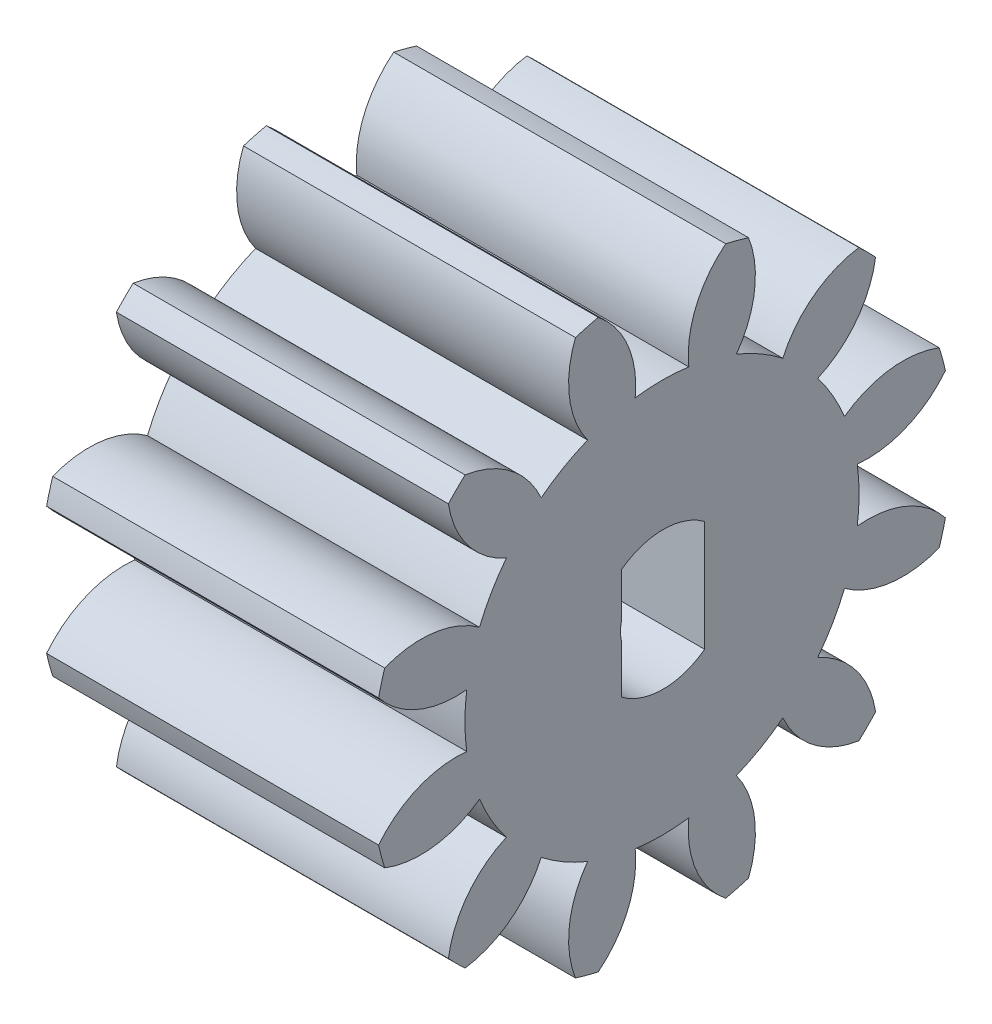
SolidWorks part; units mm, degrees
ref_plane "Plane1" through (0, 0, 0) normal (0, 0, 1) x (1, 0, 0)
ref_plane "Plane2" through (0, 0, 0) normal (0, 1, 0) x (1, 0, 0)
ref_plane "Plane3" through (0, 0, 0) normal (1, 0, 0) x (0, 0, -1)
sketch "HoldingSke" plane through (0, 0, 0) normal (0, 1, 0) x (1, 0, 0)
  line L0 (0, 0) -> (0.6521, -0.1386)
  line L1 (-15, 0) -> (100, 0) construction
  line L2 (0, 0) -> (-2.1039, 2.3779)
  line L3 (0, 0) -> (-11.863, 4.5341)
  line L4 (0, 0) -> (8.4473, 1.7955)
  line L5 (0, 0) -> (-46.8476, -17.4728)
  line L6 (0, 0) -> (-9.9476, -6.7116)
  line L7 (-2.1039, 2.3779) -> (8.6586, 51.2059)
  line L8 (-76.2, 54.61) -> (-75.7, 54.61)
  line L9 (-67.7845, 28.3722) -> (-49.3413, 33.142)
  line L10 (-76.2, 71.12) -> (104.1128, 71.12)
  line L11 (0, 0) -> (-12, 0)
  line L12 (-76.2, 101.6) -> (-76.147, 101.6)
  line L13 (24.9733, 27.94) -> (52.9518, 28.4284)
  line L14 (24.9733, 27.94) -> (24.9743, 27.94)
  line L15 (24.9733, 27.94) -> (100.4006, 29.5858)
  line L16 (-63.627, -1.5) -> (-12.827, -1.5)
  circle A0 centre (0, 0) radius 1.5
  circle A1 centre (0, 0) radius 7.124
  circle A2 centre (0, 0) radius 37.5
  circle A3 centre (0, 0) radius 1.5
  dimension "MHD" = 14.248
  dimension "Hub_dia" = 75
  dimension "Bore" = 3
  dimension "MBD" = 3
  dimension "Num_teeth" = 12
  dimension "Pitch" = 0.6667
  dimension "Overall_len" = 50
  dimension "Show_teeth" = 12
  dimension "Thickness" = 12
  dimension "OAL" = 50.0001
  dimension "T_dim" = 0.5
  dimension "Ap" = 14.5
  dimension "H" = 19.05
  dimension "Pitch_radius" = 180.3128
  dimension "Width" = 12
  dimension "Backlash" = 0.053
  dimension "Addendum_fac" = 1
  dimension "Dedendum_fac" = 1.25
  dimension "Clearance_fac" = 0.25
  dimension "Dedendum_add" = 0.001
  dimension "Module" = 1.5
sketch "BasProSke" plane through (0, 0, 0) normal (0, 1, 0) x (1, 0, 0)
  line L0 (-10, 0) -> (60, 0) construction
  line L1 (0, 0) -> (0, 10.5)
  line L2 (0, 0) -> (12, 0)
  line L3 (12, 0) -> (12, 10.5)
  line L4 (12, 10.5) -> (0, 10.5)
  dimension "Thickness" = 12
  dimension "Diameter" = 21
revolve "Base-Revolve" add sketch "BasProSke" angle 360 about L0
sketch "TooCutSke" plane through (0, 0, 0) normal (1, 0, 0) x (0, 0, -1)
  line L1 (0, 0) -> (0, 107) construction
  line L2 (0, 0) -> (-1.2674, 8.9103) construction
  line L3 (0, 0) -> (-4.625, 17.2606) construction
  line L4 (-1.2674, 8.9103) -> (-2.3125, 8.6303) construction
  arc A0 (0.9689, 7.0578) -> (-0.9689, 7.0578) centre (0, 0) ccw
  arc A1 (2.3286, 10.2646) -> (-2.3286, 10.2646) centre (0, 0) ccw
  circle A2 centre (0, 0) radius 9 construction
  circle A3 centre (0, 0) radius 8.7133 construction
  arc A4 (-0.9689, 7.0578) -> (-2.3286, 10.2646) centre (-4.5495, 7.4313) ccw
  arc A5 (2.3286, 10.2646) -> (0.9689, 7.0578) centre (4.5495, 7.4313) ccw
  dimension "Root_dia" = 14.248
  dimension "Overcut_dia" = 21.0508
  dimension "Pitch_dia" = 18
  dimension "Base_dia" = 17.4267
  dimension "Flank_rad" = 3.6
  dimension "Half_ang" = 15
  dimension "Half_CT" = 1.082
extrude "ToothCut" cut sketch "TooCutSke" along normal through all
fillet "Breaks" [suppressed] radius 0.03
fillet "RootFillets" [suppressed] radius 0.376
pattern_circular "TeethCuts" count 12 every 30 about axis through (-10, 0, 0) along (1, 0, 0) of "ToothCut", "RootFillets", "Breaks"
sketch "HubNeaOneSke" plane through (0, 0, 0) normal (-1, 0, 0) x (0, 0, 1)
  circle A0 centre (0, 0) radius 7.124
  dimension "Diameter" = 14.248
extrude "HubNearOne" [suppressed] add sketch "HubNeaOneSke" along normal blind 38.0001
sketch "HubNeaBotSke" plane through (0, 0, 0) normal (-1, 0, 0) x (0, 0, 1)
  circle A0 centre (0, 0) radius 7.124
  dimension "Diameter" = 14.248
extrude "HubNearBoth" [suppressed] add sketch "HubNeaBotSke" along normal blind 19
ref_plane "FarPln" through (12, 0, 0) normal (1, 0, 0) x (0, 0, -1)
sketch "HubFarSke" plane through (12, 0, 0) normal (1, 0, 0) x (0, 0, -1)
  circle A0 centre (0, 0) radius 7.124
  dimension "Diameter" = 14.248
extrude "HubFar" [suppressed] add sketch "HubFarSke" along normal blind 19
sketch "BorSke" plane through (0, 0, 0) normal (1, 0, 0) x (0, 0, -1)
  circle A0 centre (0, 0) radius 1.5
  dimension "Diameter" = 3
extrude "Bore" cut sketch "BorSke" along normal mid plane 100.0001
sketch "KeySke" plane through (0, 0, 0) normal (1, 0, 0) x (0, 0, -1)
  line L0 (-0.6, 0) -> (-0.6, 2)
  line L1 (-0.6, 2) -> (0.6, 2)
  line L2 (0.6, 2) -> (0.6, 0)
  line L3 (0, 0) -> (0, 34) construction
  line L4 (-0.6, 0) -> (0.6, 0)
  dimension "Offset" = 2
extrude "Keyway" [suppressed] cut sketch "KeySke" along normal mid plane 100.0001
pattern_circular "Keyway2" [suppressed] count 2 every 90 about axis through (-10, 0, 0) along (1, 0, 0)
sketch "Sketch1" plane through (12, 0, 0) normal (1, 0, 0) x (0, 0, -1)
  line L0 (1.5406, -2.0677) -> (1.5406, 1.9323)
  line L1 (-1.4594, -2.0677) -> (-1.4594, 1.9323)
  arc A0 (1.5406, -2.0677) -> (-1.4594, -2.0677) centre (0.0406, -0.0677) cw
  arc A1 (1.5406, 1.9323) -> (-1.4594, 1.9323) centre (0.0406, -0.0677) ccw
  point P6 (0, 0)
  dimension "D3" = 2.5
  dimension "D4" = 2.5
  dimension "D1" = 3
  dimension "D2" = 1.5
extrude "Cut-Extrude1" cut sketch "Sketch1" against normal blind 15
equation "' \"Module@HoldingSke\" = 6.35"
equation "' \"Num_teeth@HoldingSke\" = 12"
equation "' \"Ap@HoldingSke\" =  20"
equation "' \"Ap@HoldingSke\" = 20"
equation "' \"Width@HoldingSke\" = 0.5 * 25.4"
equation "' \"Hub_dia@HoldingSke\"= 1 * 25.4"
equation "' \"Hub_dia@HoldingSke\" = 1 * 25.4"
equation "' \"Overall_len@HoldingSke\" = 1.0 * 25.4"
equation "' \"Bore@HoldingSke\" = 0.75 * 25.4"
equation "' \"T_dim@HoldingSke\" = 0.1 * 25.4"
equation "' \"Width@KeySke\" = 0.25 * 25.4"
equation "' \"Show_teeth@HoldingSke\" = 13"
equation "' \"Backlash@HoldingSke\" = 0.009 * 25.4"
equation "' \"Addendum_fac@HoldingSke\" = 1.0"
equation "' \"Dedendum_fac@HoldingSke\" = 1.25"
equation "' \"Dedendum_add@HoldingSke\" = 0.00005 * 25.4"
equation "' \"Clearance_fac@HoldingSke\" = 0.25"
equation "\"Pitch@HoldingSke\" = 1 / \"Module@HoldingSke\""
equation "\"Overcut_dia@TooCutSke\" = (\"Num_teeth@HoldingSke\" + 2 * \"Addendum_fac@HoldingSke\") / \"Pitch@HoldingSke\" + 0.002 * 25.4"
equation "\"Pitch_dia@TooCutSke\" = \"Num_teeth@HoldingSke\" / \"Pitch@HoldingSke\""
equation "\"Base_dia@TooCutSke\" = \"Num_teeth@HoldingSke\" / \"Pitch@HoldingSke\" * cos((\"Ap@HoldingSke\"  * 3.14159265 / 180))"
equation "\"Root_dia@TooCutSke\" = (\"Num_teeth@HoldingSke\" + 2) / \"Pitch@HoldingSke\" - 2 * (\"Addendum_fac@HoldingSke\" + \"Dedendum_fac@HoldingSke\") / \"Pitch@HoldingSke\" - \"Dedendum_add@HoldingSke\" * 2"
equation "\"Half_ang@TooCutSke\" = 180 / \"Num_teeth@HoldingSke\""
equation "\"Half_CT@TooCutSke\" = \"Num_teeth@HoldingSke\" / \"Pitch@HoldingSke\" * sin((3.14159265 / 2 / \"Num_teeth@HoldingSke\")) / 2 - 7 * \"Backlash@HoldingSke\" / 4"
equation "\"Flank_rad@TooCutSke\" = \"Num_teeth@HoldingSke\" / \"Pitch@HoldingSke\" / 5"
equation "\"Radius@RootFillets\" = \"Clearance_fac@HoldingSke\" / \"Pitch@HoldingSke\" + \"Dedendum_add@HoldingSke\""
equation "\"Break_rad@Breaks\" = 0.02 / \"Pitch@HoldingSke\""
equation "\"Thickness@HoldingSke\" = \"Width@HoldingSke\""
equation "\"OAL@HoldingSke\" = \"Thickness@HoldingSke\""
equation "\"MHD@HoldingSke\" = (\"Num_teeth@HoldingSke\" + 2) / \"Pitch@HoldingSke\" - 2 * (\"Addendum_fac@HoldingSke\" + \"Dedendum_fac@HoldingSke\")  / \"Pitch@HoldingSke\" - \"Dedendum_add@HoldingSke\" * 2"
equation "\"MBD@HoldingSke\" = (\"Num_teeth@HoldingSke\" + 2) / \"Pitch@HoldingSke\" - 2 * (\"Addendum_fac@HoldingSke\" + \"Dedendum_fac@HoldingSke\")  / \"Pitch@HoldingSke\" - \"Dedendum_add@HoldingSke\" * 2 - 0.002 * 25.4"
equation "\"MHD@HoldingSke\" = ((sgn( \"MHD@HoldingSke\" - \"Hub_dia@HoldingSke\" )-1)*( \"MHD@HoldingSke\" - \"Hub_dia@HoldingSke\" ))/-2+ \"Hub_dia@HoldingSke\""
equation "\"MBD@HoldingSke\" = ((sgn( \"MBD@HoldingSke\" - \"Bore@HoldingSke\" )-1)*( \"MBD@HoldingSke\" - \"Bore@HoldingSke\" ))/-2+ \"Bore@HoldingSke\""
equation "\"OAL@HoldingSke\" = ((sgn( \"OAL@HoldingSke\" - \"Overall_len@HoldingSke\" )+1)*( \"OAL@HoldingSke\" - \"Overall_len@HoldingSke\" ))/2 + \"Overall_len@HoldingSke\" + 0.000002 * 25.4"
equation "\"Num_teeth@TeethCuts\" = int( \"Show_teeth@HoldingSke\" ) + 1"
equation "\"Num_teeth@TeethCuts\" = ((sgn( \"Num_teeth@TeethCuts\" - \"Num_teeth@HoldingSke\" )-1)*( \"Num_teeth@TeethCuts\" - \"Num_teeth@HoldingSke\" ))/-2+ \"Num_teeth@HoldingSke\""
equation "\"Num_teeth@TeethCuts\" = ((sgn( \"Num_teeth@TeethCuts\" - 2.0)+1)*( \"Num_teeth@TeethCuts\" - 2.0))/2 +2.0"
equation "\"Angle@TeethCuts\" = 360.0 / \"Num_teeth@HoldingSke\""
equation "\"Diameter@BasProSke\" = (\"Num_teeth@HoldingSke\" + 2 * \"Addendum_fac@HoldingSke\") / \"Pitch@HoldingSke\""
equation "\"Thickness@BasProSke\"  = \"Thickness@HoldingSke\""
equation "' \"Fillet_rad@BasProSke\" =  \"Thickness@HoldingSke\" * 0.05"
equation "' \"Fillet_rad@BasProSke\" = \"Thickness@HoldingSke\" * 0.05"
equation "\"MHD@HoldingSke\" = ((sgn( \"MHD@HoldingSke\" - \"Root_dia@TooCutSke\" )-1)*( \"MHD@HoldingSke\" - \"Root_dia@TooCutSke\" ))/-2+ \"Root_dia@TooCutSke\""
equation "\"Diameter@HubNeaOneSke\" = \"MHD@HoldingSke\""
equation "\"Length@HubNearOne\" = \"OAL@HoldingSke\" - \"Thickness@BasProSke\""
equation "\"Diameter@HubNeaBotSke\" = \"MHD@HoldingSke\""
equation "\"Length@HubNearBoth\" = ( \"OAL@HoldingSke\" - \"Thickness@BasProSke\" ) / 2.0"
equation "\"Thickness@FarPln\" = \"Thickness@BasProSke\""
equation "\"Diameter@HubFarSke\" = \"MHD@HoldingSke\""
equation "\"Length@HubFar\" = ( \"OAL@HoldingSke\" - \"Thickness@BasProSke\" ) / 2.0"
equation "\"Diameter@BorSke\" = \"MBD@HoldingSke\""
equation "\"D1@Bore\" = \"OAL@HoldingSke\" * 2.0"
equation "\"D1@Keyway\" = \"OAL@HoldingSke\" * 2.0"
equation "\"Offset@KeySke\" = \"T_dim@HoldingSke\" + \"MBD@HoldingSke\" / 2.0"
